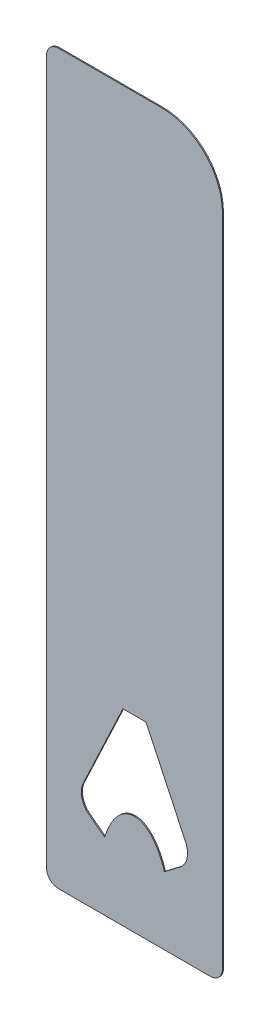
SolidWorks part; units mm, degrees
material "3M 9474LE (300LSE)"
ref_plane "Front Plane" through (0, 0, 0) normal (0, 0, 1) x (1, 0, 0)
ref_plane "Top Plane" through (0, 0, 0) normal (0, 1, 0) x (1, 0, 0)
ref_plane "Right Plane" through (0, 0, 0) normal (1, 0, 0) x (0, 0, -1)
other "Configuration Table"
sketch "Sketch20" plane through (0, 0, 0) normal (0, 0, 1) x (1, 0, 0)
  line L0 (0, 60) -> (0, -60) construction
  line L1 (-12.5, 60) -> (4.5, 60)
  line L2 (-14.5, 58) -> (-14.5, -58)
  line L3 (-12.5, -60) -> (12.5, -60)
  line L4 (14.5, 50) -> (14.5, -58)
  line L5 (-14.5, 60) -> (14.5, -60) construction
  line L6 (-14.5, -60) -> (14.5, 60) construction
  line L7 (-14.5, 0) -> (14.5, 0) construction
  line L8 (0, -55) -> (0, 55) construction
  arc A0 (-14.5, -58) -> (-12.5, -60) centre (-12.5, -58) ccw
  arc A1 (12.5, -60) -> (14.5, -58) centre (12.5, -58) ccw
  arc A2 (4.5, 60) -> (14.5, 50) centre (4.5, 50) cw
  arc A3 (-12.5, 60) -> (-14.5, 58) centre (-12.5, 58) ccw
  point P0 (0, 0)
extrude "Boss-Extrude6" add sketch "Sketch20" along normal blind 0.17
sketch "Sketch14" plane through (0, 0, 0.17) normal (0, 0, 1) x (1, 0, 0)
  line L44 (0, -29) -> (0, -43.4) construction
  line L45 (-1.9, -29) -> (1.9, -29)
  line L46 (1.9, -29) -> (8.375, -42.75)
  line L47 (7.4, -46.9731) -> (4.925, -48.85)
  line L48 (-7.4, -46.9731) -> (-4.925, -48.85)
  line L49 (-1.9, -29) -> (-8.375, -42.75)
  line L51 (0, -60) -> (0, -29) construction
  line L52 (-12.5, -60) -> (12.5, -60) construction
  spline S0 degree 3 poles (-4.925, -48.85) (-3.9562, -45.6317) (-2.1467, -43.4006) (0, -43.4) knots 5.001928 5.001928 5.001928 5.001928 5.999902 5.999902 5.999902 5.999902
  spline S1 degree 3 poles (8.375, -42.75) (8.614, -43.206) (8.7497, -43.7369) (8.75, -44.3) knots 2 2 2 2 3 3 3 3
  spline S2 degree 3 poles (8.75, -44.3) (8.7506, -45.4277) (8.2114, -46.4163) (7.4, -46.9731) knots 3 3 3 3 3.998305 3.998305 3.998305 3.998305
  spline S3 degree 3 poles (4.925, -48.85) (3.9562, -45.6317) (2.1467, -43.4006) (0, -43.4) knots 5.001928 5.001928 5.001928 5.001928 5.999902 5.999902 5.999902 5.999902
  spline S4 degree 3 poles (-8.75, -44.3) (-8.7506, -45.4277) (-8.2114, -46.4163) (-7.4, -46.9731) knots 3 3 3 3 3.998305 3.998305 3.998305 3.998305
  spline S5 degree 3 poles (-8.375, -42.75) (-8.614, -43.206) (-8.7497, -43.7369) (-8.75, -44.3) knots 2 2 2 2 3 3 3 3
  point P13 (0, 0)
  point P16 (8.375, -25.4312)
  point P19 (0, 0)
  dimension "D3" = 17.5
  dimension "D4" = 14.8
  dimension "D7" = 9.85
  dimension "D6" = 15.3
  dimension "D1" = 3.8
  dimension "D2" = 16.75
  dimension "D5" = 13.75
  dimension "D8" = 31
extrude "Cut-Extrude4" cut sketch "Sketch14" against normal through all
